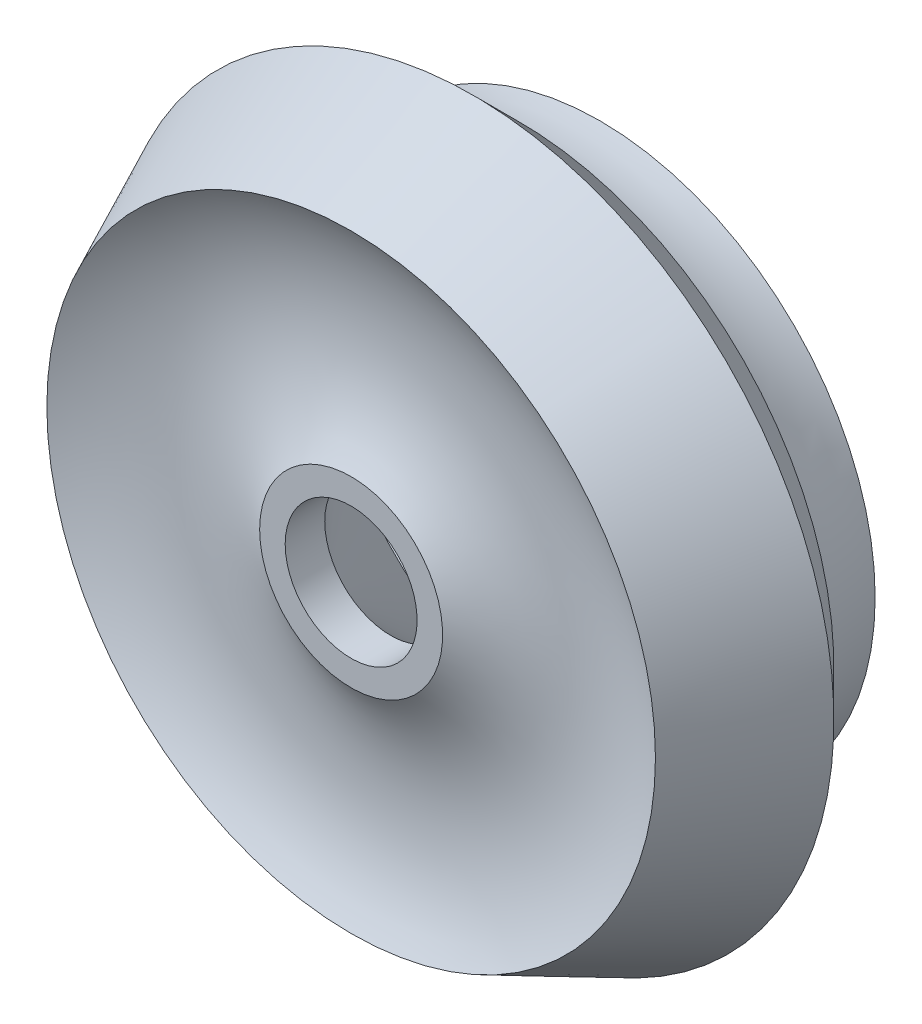
SolidWorks part; units mm, degrees
ref_plane "Front Plane" through (0, 0, 0) normal (0, 0, 1) x (1, 0, 0)
ref_plane "Top Plane" through (0, 0, 0) normal (0, 1, 0) x (1, 0, 0)
ref_plane "Right Plane" through (0, 0, 0) normal (1, 0, 0) x (0, 0, -1)
sketch "Hatch Sketch" plane through (0, 0, 0) normal (1, 0, 0) x (0, 0, -1)
  line L0 (-1132.4588, -713.8513) -> (-758.9546, -713.8513) construction
  line L1 (546.1, 0) -> (0, 0) construction
  line L2 (495, 230.6517) -> (495, 0) construction
  line L3 (495, 230.6517) -> (0, 0) construction
  line L4 (587.2743, 273.6481) -> (495, 230.6517)
  line L5 (475, 0) -> (735, 0) construction
  line L6 (525, 50) -> (475, 0) construction
  line L7 (525, 50) -> (495, 50)
  line L8 (525, 50) -> (658.8478, 183.8478)
  line L9 (495, 69.3483) -> (495, 50)
  line L10 (683.5965, 208.5965) -> (658.8478, 183.8478) construction
  line L11 (683.5965, 208.5965) -> (683.5965, 155.2015)
  line L12 (621.8227, 239.0997) -> (667.9612, 192.9612) construction
  line L13 (621.8227, 239.0997) -> (606.8256, 224.1027)
  line L14 (621.8227, 239.0997) -> (587.2743, 273.6481)
  arc A0 (546.1, 0) -> (495, 230.6517) centre (0, 0) ccw construction
  arc A1 (609.6, 0) -> (552.5581, 257.4717) centre (0, 0) ccw construction
  arc A2 (647.9, 0) -> (587.2743, 273.6481) centre (0, 0) ccw construction
  arc A3 (683.5965, 155.2015) -> (658.8478, 183.8478) centre (475, 0) ccw
  arc A4 (495, 69.3483) -> (495, 230.6517) centre (368.5275, 150) ccw
  arc A5 (735, 0) -> (540.171, 251.6997) centre (475, 0) ccw construction
  arc A6 (606.8256, 224.1027) -> (683.5965, 208.5965) centre (667.6682, 327.5347) ccw
  dimension "D1" = 546.1
  dimension "D3" = 609.6
  dimension "D4" = 647.9
  dimension "D5" = 260
  dimension "D7" = 475
  dimension "D8" = 150
  dimension "D10" = 35
  dimension "D11" = 120
  dimension "D2" = 495
  dimension "D6" = 45
  dimension "D9" = 30
revolve "Hatch Revolution" add sketch "Hatch Sketch" angle 360 about L1
